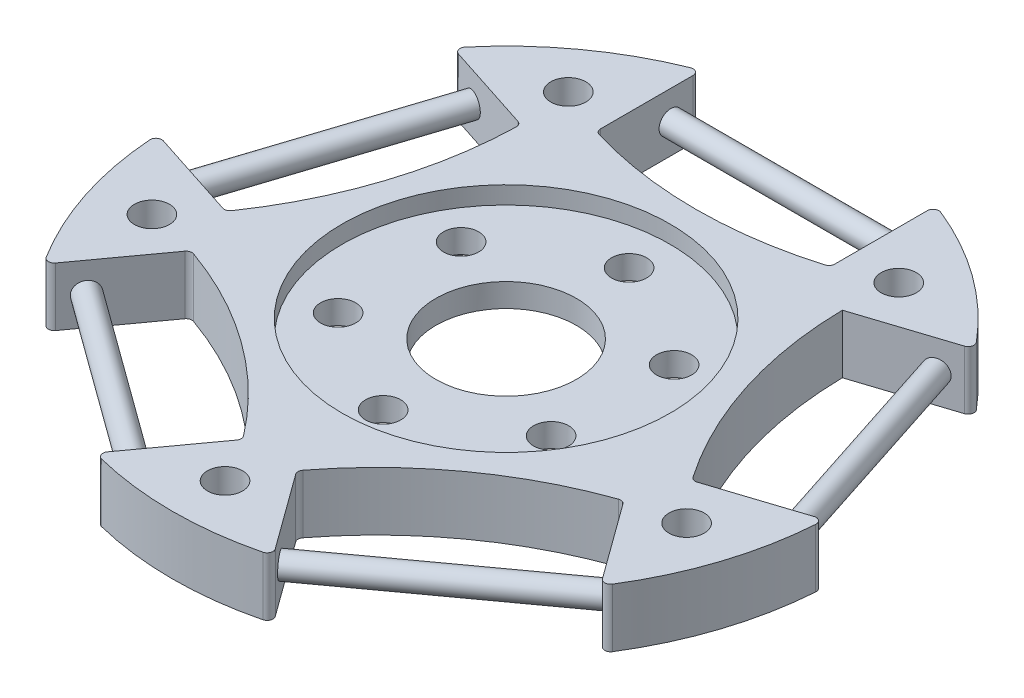
SolidWorks part; units mm, degrees
other "Camera1"
ref_plane "Front Plane" through (0, 0, 0) normal (0, 0, 1) x (1, 0, 0)
ref_plane "Top Plane" through (0, 0, 0) normal (0, 1, 0) x (1, 0, 0)
ref_plane "Right Plane" through (0, 0, 0) normal (1, 0, 0) x (0, 0, -1)
sketch "Sketch1" plane through (0, 0, 0) normal (0, 1, 0) x (1, 0, 0)
  line L0 (0, 0) -> (0, 50000) construction
  line L1 (0, 0) -> (-50000, 0) construction
  circle A0 centre (0, 0) radius 28.5
  dimension "D1" = 57
extrude "Boss-Extrude1" add sketch "Sketch1" along normal blind 5
sketch "Sketch2" plane through (0, 5, 0) normal (0, 1, 0) x (1, 0, 0)
  line L0 (0, 0) -> (13.4182, 0) construction
  line L1 (0, 0) -> (0, 50000) construction
  line L2 (10, 26.688) -> (10, 17.688)
  line L3 (-10, 26.688) -> (-10, 17.688)
  circle A0 centre (0, 0) radius 28.5 construction
  arc A1 (-10, 17.688) -> (10, 17.688) centre (0, 50.0973) ccw
  arc A2 (-10, 26.688) -> (10, 26.688) centre (0, 0) cw
  dimension "D1" = 9
  dimension "D2" = 10
extrude "Cut-Extrude1" cut sketch "Sketch2" against normal through all
pattern_circular "CirPattern1" count 5 over 360 about axis through (0, 0, 0) along (0, 1, 0) of "Cut-Extrude1"
sketch "Sketch3" plane through (0, 5, 0) normal (0, 1, 0) x (1, 0, 0)
  circle A0 centre (0, 0) radius 14
  dimension "D1" = 28
extrude "Cut-Extrude2" cut sketch "Sketch3" against normal blind 1.5
ref_plane "Plane1" through (0, 2.5, 0) normal (0, 1, 0) x (1, 0, 0)
mirror "Mirror1" about plane through (0, 2.5, 0) normal (0, 1, 0) of "Cut-Extrude2"
sketch "Sketch4" plane through (0, 3.5, 0) normal (0, 1, 0) x (1, 0, 0)
  circle A0 centre (0, 10.5) radius 1.5
  circle A1 centre (0, 0) radius 10.5 construction
  circle A2 centre (9.0933, 5.25) radius 1.5
  circle A3 centre (9.0933, -5.25) radius 1.5
  circle A4 centre (0, -10.5) radius 1.5
  circle A5 centre (-9.0933, -5.25) radius 1.5
  circle A6 centre (-9.0933, 5.25) radius 1.5
  circle A7 centre (0, 0) radius 6
  point P18 (0, 0)
  dimension "D2" = 3
  dimension "D4" = 12
  dimension "D1" = 10.5
  dimension "D3" = 6
extrude "Cut-Extrude3" cut sketch "Sketch4" against normal through all
sketch "Sketch5" plane through (0, 5, 0) normal (0, 1, 0) x (1, 0, 0)
  line L0 (0, 0) -> (0, -50000) construction
  circle A0 centre (0, -24) radius 1.5
  dimension "D1" = 24
extrude "Cut-Extrude4" cut sketch "Sketch5" against normal through all
pattern_circular "CirPattern2" count 5 over 360 about axis through (0, 0, 0) along (0, 1, 0) of "Cut-Extrude4"
fillet "Fillet1" radius 0.5 19 edges at (10, 2.5, -17.688) (-10, 2.5, -17.688) (-13.7321, 2.5, -14.9765) (-19.9125, 2.5, 4.0447) (-18.4869, 2.5, 8.4321) (-2.3066, 2.5, 20.1878) (19.9125, 2.5, 4.0447) (18.4869, 2.5, 8.4321) (2.3066, 2.5, 20.1878) (10, 2.5, -26.688) (22.2916, 2.5, -17.7576) (28.472, 2.5, 1.2635) (23.777, 2.5, 15.7132) (7.5967, 2.5, 27.4689) (-7.5967, 2.5, 27.4689) (-23.777, 2.5, 15.7132) (-28.472, 2.5, 1.2635) (-22.2916, 2.5, -17.7576) (-10, 2.5, -26.688)
sketch "Sketch7" plane through (-8.0902, 0, -5.8779) normal (0.809, 0, 0.5878) x (0.5878, 0, -0.809)
  line L1 (-33.8543, 2.5) -> (-18.0591, 2.5) construction
  line L3 (-18.0591, 0) -> (-18.0591, 5) construction
  line L5 (-22.0079, 10) -> (-22.0079, 0) construction
  line L7 (-18.0591, 0) -> (-25.9567, 0) construction
  circle A0 centre (-24.0591, 2.5) radius 1
  point P0 (-25.9567, 2.5)
  point P1 (-22.0079, 5)
  dimension "D1" = 2
  dimension "D2" = 6
extrude "Boss-Extrude2" add sketch "Sketch7" along normal up to next
pattern_circular "CirPattern3" count 5 over 360 about axis through (0, 3.5, 0) along (0, 1, 0) of "Boss-Extrude2"
